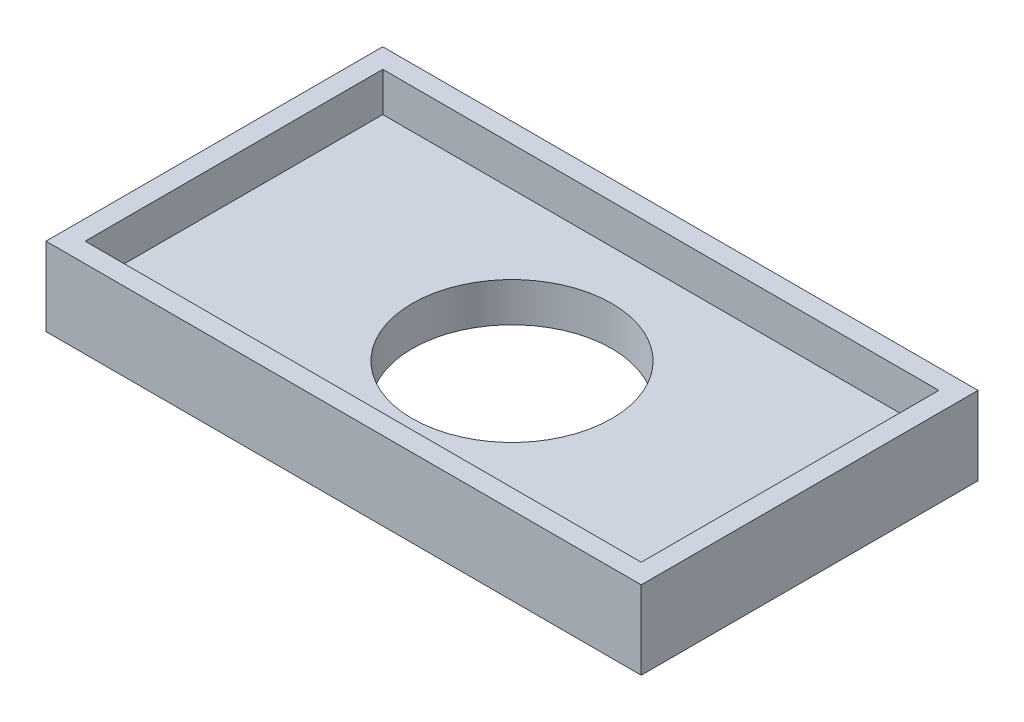
SolidWorks part; units mm, degrees
ref_plane "Front Plane" through (0, 0, 0) normal (0, 0, 1) x (1, 0, 0)
ref_plane "Top Plane" through (0, 0, 0) normal (0, 1, 0) x (1, 0, 0)
ref_plane "Right Plane" through (0, 0, 0) normal (1, 0, 0) x (0, 0, -1)
sketch "Sketch1" plane through (0, 0, 0) normal (0, 1, 0) x (1, 0, 0)
  line L1 (-76, 43) -> (76, 43)
  line L2 (-76, 43) -> (-76, -43)
  line L3 (-76, -43) -> (76, -43)
  line L4 (76, 43) -> (76, -43)
  line L5 (-76, 43) -> (76, -43) construction
  line L6 (-76, -43) -> (76, 43) construction
  point P0 (0, 0)
  dimension "D1" = 152
  dimension "D2" = 86
extrude "Boss-Extrude1" add sketch "Sketch1" along normal blind 10
sketch "Sketch2" plane through (0, 10, 0) normal (0, 1, 0) x (1, 0, 0)
  line L1 (-71, 38) -> (71, 38)
  line L2 (-71, 38) -> (-71, -38)
  line L3 (-71, -38) -> (71, -38)
  line L4 (71, 38) -> (71, -38)
  line L5 (-71, 38) -> (71, -38) construction
  line L6 (-71, -38) -> (71, 38) construction
  line L7 (-76, 43) -> (76, 43)
  line L8 (-76, 43) -> (-76, -43)
  line L9 (-76, -43) -> (76, -43)
  line L10 (76, 43) -> (76, -43)
  line L11 (-76, 43) -> (76, -43) construction
  line L12 (-76, -43) -> (76, 43) construction
  point P0 (0, 0)
  point P6 (0, 0)
  dimension "D1" = 142
  dimension "D2" = 76
extrude "Boss-Extrude2" add sketch "Sketch2" along normal blind 10
hole_wizard "2.0350-40 UNS Tapped Hole1" positions "Sketch7" profile "Sketch6" tap size "2.0350-40 UNS" standard "ANSI Inch"
sketch "Sketch7" plane through (0, 0, 0) normal (0, -1, 0) x (-1, 0, 0)
  point P0 (0, 0)
sketch "Sketch6" plane through (0, 0, 0) normal (1, 0, 0) x (0, 0, -1)
  line L0 (0, 0) -> (0, 106.56)
  line L1 (0, 106.56) -> (25.4778, 106.56)
  line L2 (25.4778, 106.56) -> (25.4778, 0)
  line L5 (25.4778, 0) -> (0, 0)
  line L10 (0, 106.56) -> (-25.4778, 106.56) construction
  line L11 (0, -6.35) -> (0, 107.95) construction
  dimension "Tap Drill Dia." = 50.9556
  dimension "Tap Drill Depth" = 106.56
  dimension "Drill Angle" = 180
cosmetic thread "Hole Thread1" parameters "D1"=10, "D2"=51.689
